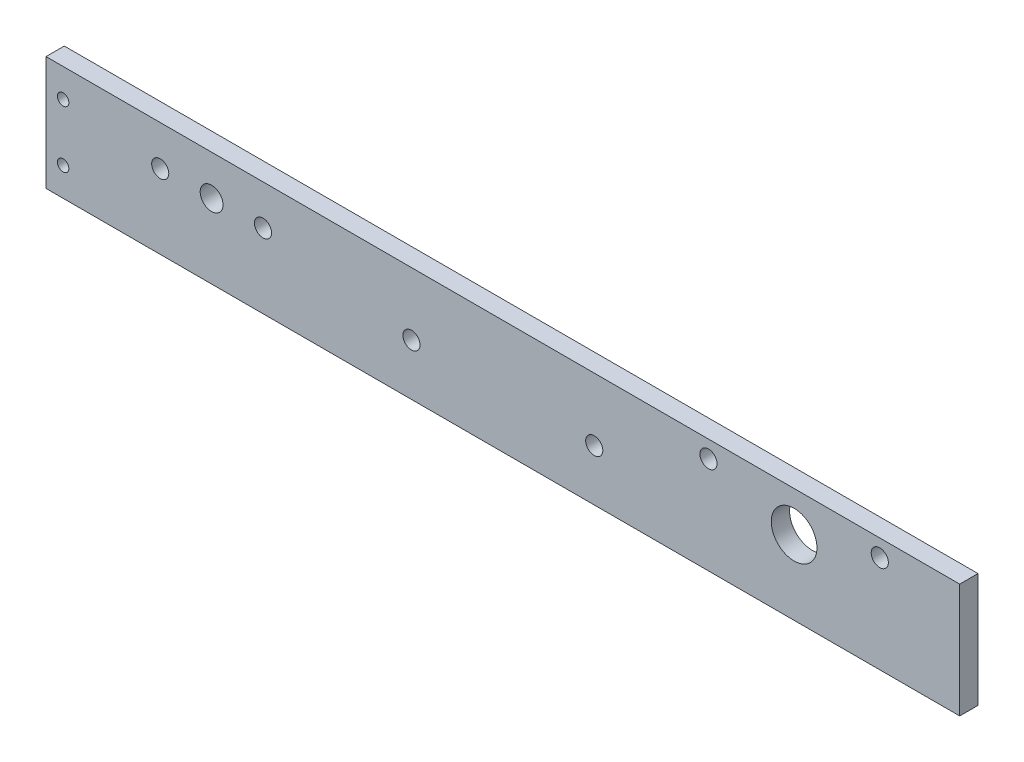
SolidWorks part; units mm, degrees
material "Balsa"
ref_plane "Front Plane" through (0, 0, 0) normal (0, 0, 1) x (1, 0, 0)
ref_plane "Top Plane" through (0, 0, 0) normal (0, 1, 0) x (1, 0, 0)
ref_plane "Right Plane" through (0, 0, 0) normal (1, 0, 0) x (0, 0, -1)
ref_plane "Plane1" through (0, 0, 10) normal (0, 0, 1) x (1, 0, 0)
sketch "Sketch2" plane through (0, -10, 10) normal (0, 0, -1) x (1, 0, 0)
  line L1 (0, -10) -> (160, -10)
  line L2 (0, -10) -> (0, 10)
  line L3 (0, 10) -> (160, 10)
  line L4 (160, -10) -> (160, 10)
  dimension "D1" = 20
  dimension "D2" = 160
extrude "Boss-Extrude1" add sketch "Sketch2" along normal blind 3.2
sketch "Sketch4" plane through (0, 0, 0) normal (0, 1, 0) x (1, 0, 0)
  line L0 (0, -10) -> (160, -10) construction
  line L1 (0, -6.8) -> (80, -6.8)
  line L2 (0, -6.8) -> (0, -10)
  line L3 (0, -10) -> (80, -10)
  line L4 (80, -6.8) -> (80, -10)
  line L5 (160, -6.8) -> (160, -10) construction
  dimension "D1" = 80
  dimension "D2" = 80
sketch "Sketch5" plane through (0, 0, 10) normal (0, 0, 1) x (1, 0, 0)
  line L0 (102, 2.15) -> (102, -20)
  line L1 (102, 0) -> (102, 4.3) construction
  line L2 (160, -20) -> (0, -20) construction
  line L3 (58, 2.15) -> (58, -20)
  line L4 (58, 0) -> (58, 4.3) construction
  line L7 (29, -7) -> (131, -7)
  line L9 (0, 0) -> (160, 0) construction
  circle A0 centre (131, -7) radius 4
  circle A1 centre (29, -7) radius 2
  dimension "D1" = 7
  dimension "D2" = 8
extrude "Cut-Extrude1" cut sketch "Sketch5" against normal through all both and the other way through all contours A0 | A1
sketch "Sketch6" plane through (0, 0, 10) normal (0, 0, 1) x (1, 0, 0)
  circle A0 centre (96, -11) radius 1.5
  circle A1 centre (64, -11) radius 1.5
  dimension "D1" = 32
extrude "Cut-Extrude2" cut sketch "Sketch6" against normal blind 10
sketch "Sketch7" plane through (0, 0, 10) normal (0, 0, 1) x (1, 0, 0)
  circle A0 centre (3, -15) radius 1
  circle A1 centre (3, -5) radius 1
  dimension "D1" = 2
extrude "Cut-Extrude3" cut sketch "Sketch7" against normal through all both and the other way through all
sketch "Sketch8" plane through (0, 0, 6.8) normal (0, 0, -1) x (-1, 0, 0)
  circle A0 centre (-116, -3) radius 1.5 construction
  circle A1 centre (-116, -3) radius 1.5
  circle A2 centre (-146, -3) radius 1.5 construction
  circle A3 centre (-146, -3) radius 1.5
extrude "Cut-Extrude4" cut sketch "Sketch8" against normal blind 10
sketch "Sketch9" plane through (0, 0, 10) normal (0, 0, 1) x (1, 0, 0)
  circle A0 centre (38, -7) radius 1.5
  circle A1 centre (20, -7) radius 1.5
extrude "Cut-Extrude5" cut sketch "Sketch9" against normal blind 10
